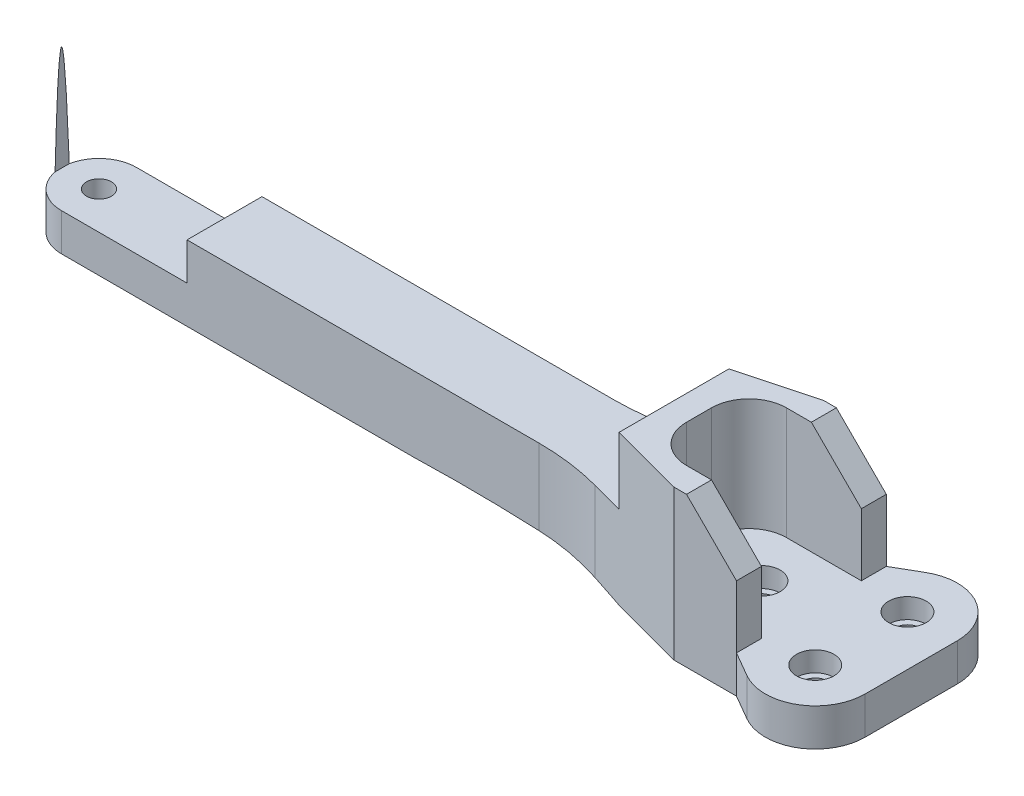
SolidWorks part; units mm, degrees
ref_plane "Front Plane" through (0, 0, 0) normal (0, 0, 1) x (1, 0, 0)
ref_plane "Top Plane" through (0, 0, 0) normal (0, 1, 0) x (1, 0, 0)
ref_plane "Right Plane" through (0, 0, 0) normal (1, 0, 0) x (0, 0, -1)
sketch "Sketch1" plane through (0, 0, 0) normal (0, 1, 0) x (1, 0, 0)
  line L3 (0, -15) -> (179, -15)
  line L6 (217.0073, 18.4074) -> (260.2715, 30)
  line L9 (260.2715, 30) -> (285.2715, 30)
  line L10 (285.2715, 30) -> (285.2715, 20)
  line L21 (285.2715, 20) -> (255.2715, 20)
  line L22 (0, 15) -> (191.1254, 15)
  line L23 (0, 0) -> (251.9891, 0) construction
  line L24 (240.2715, 5) -> (240.2715, -5)
  line L25 (285.2715, -20) -> (255.2715, -20)
  line L26 (285.2715, -30) -> (285.2715, -20)
  line L27 (260.2715, -30) -> (285.2715, -30)
  line L28 (217.0073, -18.4074) -> (260.2715, -30)
  line L29 (0, -15) -> (191.1254, -15)
  line L30 (328.8402, 18.46) -> (328.8402, -18.46)
  line L32 (285.2715, 30) -> (302.2964, 37.4926)
  line L33 (251.9891, 0) -> (328.8402, 0) construction
  line L34 (285.2715, -30) -> (301.9598, -37.3444)
  arc A0 (217.0073, 18.4074) -> (191.1254, 15) centre (191.1254, 115) cw
  arc A2 (240.2715, 5) -> (255.2715, 20) centre (255.2715, 5) cw
  arc A3 (240.2715, -5) -> (255.2715, -20) centre (255.2715, -5) ccw
  arc A4 (217.0073, -18.4074) -> (191.1254, -15) centre (191.1254, -115) ccw
  arc A5 (0, 15) -> (0, -15) centre (0, 0) ccw
  circle A6 centre (0, 0) radius 5
  circle A7 centre (308.8002, 18.46) radius 8.8022
  circle A8 centre (308.8002, -18.46) radius 8.9198
  arc A9 (328.8402, 18.46) -> (300.7279, 36.8023) centre (308.8002, 18.46) ccw
  arc A10 (300.7279, -36.8023) -> (328.8402, -18.46) centre (308.8002, -18.46) ccw
  point P19 (240.2715, 0)
  dimension "D2" = 10
  dimension "D3" = 100
  dimension "D9" = 36.92
  dimension "D6" = 15
  dimension "D11" = 77
  dimension "D12" = 45
  dimension "D1" = 30
  dimension "D4" = 20
  dimension "D5" = 10
  dimension "D7" = 25
  dimension "D8" = 165
  dimension "D10" = 48.46
extrude "Boss-Extrude1" add sketch "Sketch1" against normal blind 60 contours L22 A5 L3 L29 A4 L28 L27 L26 L25 A3 L24 A2 L21 L10 L9 L6 A0 A6
ref_plane "Plane1" through (0, -60, 0) normal (0, 1, 0) x (1, 0, 0)
sketch "Sketch4" plane through (0, -60, 0) normal (0, 1, 0) x (1, 0, 0)
  line L0 (260.2715, 30) -> (285.2715, 30) construction
  line L1 (325.2715, 18.46) -> (325.2715, -44.7783)
  line L2 (285.2715, -30) -> (285.2715, -20)
  line L3 (285.2715, 30) -> (295.2624, 35.7753)
  line L4 (285.2715, -30) -> (295.2624, -35.7753)
  line L5 (260.2715, 30) -> (260.2715, -30) construction
  line L6 (285.2715, 30) -> (285.2715, 20)
  line L12 (285.2715, 20) -> (255.2715, 20)
  line L14 (285.2715, -20) -> (255.2715, -20)
  line L15 (240.2715, 5) -> (240.2715, -5)
  arc A0 (325.2715, 18.46) -> (295.2624, 35.7753) centre (305.2715, 18.46) ccw
  arc A1 (295.2624, -35.7753) -> (325.2715, -18.46) centre (305.2715, -18.46) ccw
  arc A2 (255.2715, -20) -> (240.2715, -5) centre (255.2715, -5) cw
  arc A3 (240.2715, 5) -> (255.2715, 20) centre (255.2715, 5) cw
  point P29 (240.2715, 20)
  dimension "D1" = 45
  dimension "D5" = 15
  dimension "D2" = 36.92
  dimension "D3" = 48.46
  dimension "D4" = 65
extrude "Boss-Extrude2" add sketch "Sketch4" along normal blind 15 contours L5 L12 A3 L15 A2 L14 | L12 L5 L14 L2 L4 A1 L1 A0 L3 L6
sketch "Sketch6" plane through (0, -45, 0) normal (0, 1, 0) x (1, 0, 0)
  line L0 (305.2715, 38.46) -> (305.2715, -38.46) construction
  line L2 (260.2715, 30) -> (285.2715, 30) construction
  line L3 (325.2715, 18.46) -> (325.2715, -18.46) construction
  arc A0 (325.2715, 18.46) -> (295.2624, 35.7753) centre (305.2715, 18.46) ccw construction
  arc A1 (295.2624, -35.7753) -> (325.2715, -18.46) centre (305.2715, -18.46) ccw construction
  point P11 (305.2715, 18.46)
  point P14 (305.2715, -18.46)
  point P16 (265.2715, 0)
  dimension "D1" = 30
  dimension "D2" = 60
hole_wizard "CBORE for M5 Hex Head Bolt1" positions "Sketch6" profile "Sketch8" counterbore size "M5" standard "ISO" end condition through all
sketch "Sketch8" plane through (265.2715, -45, 0) normal (1, 0, 0) x (0, 0, 1)
  line L0 (0, 0) -> (0, 15)
  line L1 (0, 15) -> (5, 15)
  line L3 (5, 15) -> (5, 8)
  line L4 (5, 8) -> (7.5, 8)
  line L5 (7.5, 8) -> (7.5, 0)
  line L7 (7.5, 0) -> (0, 0)
  line L11 (0, -6.35) -> (0, 107.95) construction
  dimension "Thru Hole Dia." = 10
  dimension "Thru Hole Depth" = 15
  dimension "C'Bore Dia." = 15
  dimension "C'Bore Depth" = 8
ref_plane "Plane2" through (0, 0, 30) normal (0, 0, 1) x (1, 0, 0)
chamfer "Chamfer1" distance 20 angle 45 2 edges at (285.2715, 0, -25) (285.2715, 0, 25)
sketch "Sketch9" plane through (0, 0, 30) normal (0, 0, 1) x (1, 0, 0)
  line L1 (-14.7285, -56.7665) -> (141.26, -56.7665)
  line L4 (50.2715, -26.7681) -> (230.2715, -26.7681)
  line L5 (230.2715, -26.7681) -> (230.2715, 0)
  line L6 (50.2715, -26.7681) -> (50.2715, -41.7665)
  line L7 (0, 0) -> (191.1254, 0) construction
  line L8 (230.2715, 0) -> (265.2715, 0)
  line L9 (265.2715, 0) -> (285.2715, -20)
  line L10 (285.2715, -20) -> (285.2715, -60)
  line L12 (-14.7285, -41.7665) -> (-15, 0)
  line L13 (50.2715, -41.7665) -> (-14.7285, -41.7665)
  line L14 (-14.7285, -41.7665) -> (-14.7285, -56.7665)
  line L17 (217.0073, -60) -> (260.2715, -60) construction
  line L18 (230, -60) -> (285.2715, -60)
  line L19 (65.2715, -34.2681) -> (50.2715, -49.2681)
  line L20 (50.2715, -49.2681) -> (80.2715, -49.2681)
  line L21 (80.2715, -49.2681) -> (65.2715, -34.2681)
  line L22 (102.2715, -49.2681) -> (132.2715, -49.2681)
  line L23 (132.2715, -49.2681) -> (117.2715, -34.2681)
  line L24 (117.2715, -34.2681) -> (102.2715, -49.2681)
  line L25 (154.2715, -49.2681) -> (184.2715, -49.2681)
  line L26 (184.2715, -49.2681) -> (169.2715, -34.2681)
  line L27 (169.2715, -34.2681) -> (154.2715, -49.2681)
  line L28 (76.2715, -34.2681) -> (91.2715, -49.2681)
  line L29 (91.2715, -49.2681) -> (106.2715, -34.2681)
  line L30 (106.2715, -34.2681) -> (76.2715, -34.2681)
  line L31 (143.2715, -49.2681) -> (158.2715, -34.2681)
  line L32 (128.2715, -34.2681) -> (143.2715, -49.2681)
  line L33 (158.2715, -34.2681) -> (128.2715, -34.2681)
  line L34 (195.2715, -49.2681) -> (210.2715, -34.2681)
  line L35 (180.2715, -34.2681) -> (195.2715, -49.2681)
  line L36 (210.2715, -34.2681) -> (180.2715, -34.2681)
  line L37 (-15, 0) -> (230.2715, 0)
  line L38 (-14.7285, -56.7665) -> (-15, -60)
  line L39 (-15, -60) -> (230, -60)
  arc A1 (141.26, -56.7665) -> (230, -60) centre (161.2105, -728.54) cw
  dimension "D1" = 15
  dimension "D2" = 30
  dimension "D3" = 65
  dimension "D4" = 245
  dimension "D5" = 45
  dimension "D7" = 65
  dimension "D8" = 300
  dimension "D10" = 45
  dimension "D11" = 11
  dimension "D9" = 3
  dimension "D12" = 3
extrude "Cut-Extrude3" cut sketch "Sketch9" against normal through all contours L37 L12 L13 L6 L4 L5 | A1 L1 L38 L39
